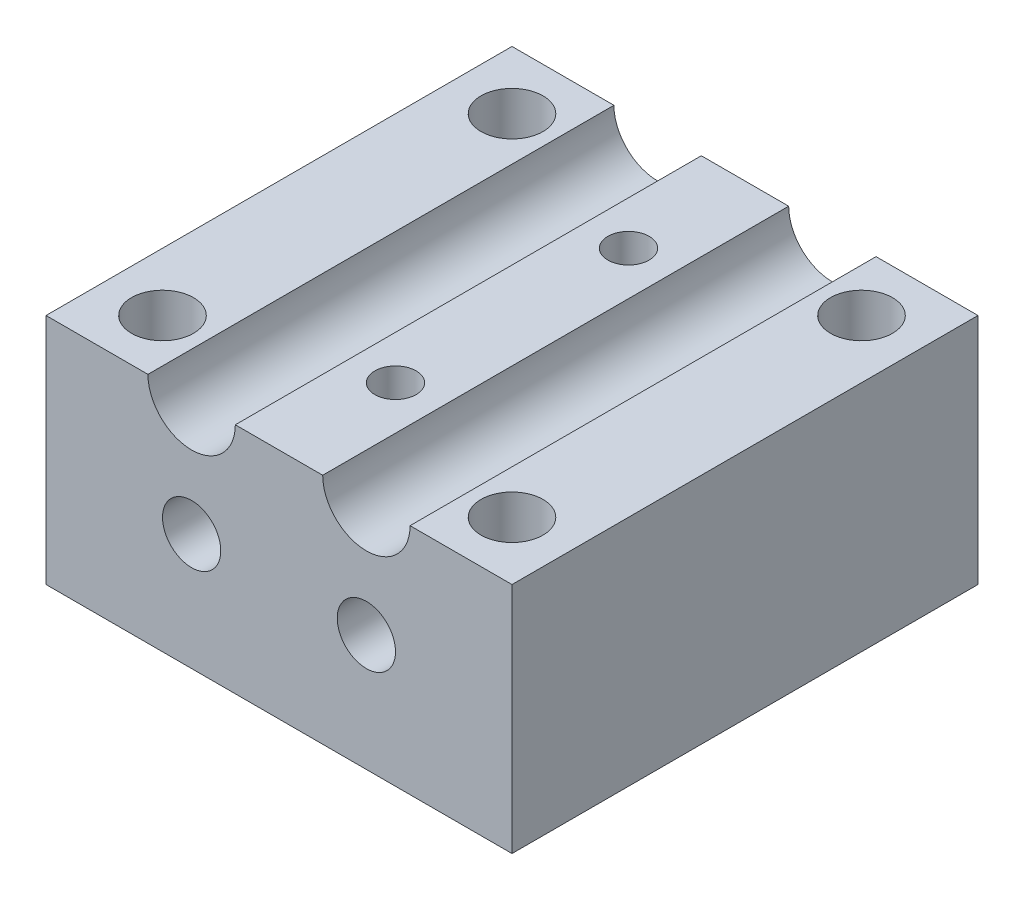
SolidWorks part; units mm, degrees
ref_plane "Front Plane" through (0, 0, 0) normal (0, 0, 1) x (1, 0, 0)
ref_plane "Top Plane" through (0, 0, 0) normal (0, 1, 0) x (1, 0, 0)
ref_plane "Right Plane" through (0, 0, 0) normal (1, 0, 0) x (0, 0, -1)
sketch "Sketch1" plane through (0, 0, 0) normal (0, 1, 0) x (1, 0, 0)
  line L1 (25.4, 25.4) -> (-25.4, 25.4)
  line L2 (25.4, 25.4) -> (25.4, -25.4)
  line L3 (25.4, -25.4) -> (-25.4, -25.4)
  line L4 (-25.4, 25.4) -> (-25.4, -25.4)
  line L5 (25.4, 25.4) -> (-25.4, -25.4) construction
  line L6 (25.4, -25.4) -> (-25.4, 25.4) construction
  point P0 (0, 0)
  dimension "D1" = 50.8
  dimension "D2" = 50.8
extrude "Boss-Extrude1" add sketch "Sketch1" along normal blind 25.4
sketch "Sketch2" plane through (0, 0, 25.4) normal (0, 0, 1) x (1, 0, 0)
  line L0 (-25.4, 25.4) -> (25.4, 25.4) construction
  line L1 (25.4, 25.4) -> (-25.4, 25.4) construction
  circle A0 centre (-9.525, 25.4) radius 4.7625
  circle A1 centre (9.525, 25.4) radius 4.7625
  point P6 (0, 25.4)
  dimension "D1" = 9.525
  dimension "D2" = 19.05
  dimension "D3" = 9.525
extrude "Cut-Extrude1" cut sketch "Sketch2" against normal through all
hole_wizard "1/4 Clearance Hole1" positions "Sketch5" profile "Sketch4" hole size "1/4" standard "ANSI Inch" end condition through all
sketch "Sketch5" plane through (0, 25.4, 0) normal (0, 1, 0) x (1, 0, 0)
  point P0 (-19.05, 19.05)
  point P2 (-19.05, -19.05)
  point P4 (19.05, -19.05)
  point P6 (19.05, 19.05)
sketch "Sketch4" plane through (-19.05, 25.4, -19.05) normal (1, 0, 0) x (0, 0, 1)
  line L0 (0, 0) -> (0, 25.4)
  line L1 (0, 25.4) -> (3.3782, 25.4)
  line L2 (3.3782, 25.4) -> (3.3782, 0)
  line L5 (3.3782, 0) -> (0, 0)
  line L11 (0, -6.35) -> (0, 107.95) construction
  dimension "Thru Hole Dia." = 6.7564
  dimension "Thru Hole Depth" = 25.4
sketch "Sketch6" plane through (0, 0, 25.4) normal (0, 0, 1) x (1, 0, 0)
  line L0 (-25.4, 25.4) -> (-14.2875, 25.4) construction
  circle A0 centre (-9.525, 12.7) radius 3.175
  circle A1 centre (9.525, 12.7) radius 3.175
  dimension "D1" = 6.35
  dimension "D2" = 19.05
  dimension "D4" = 9.525
  dimension "D5" = 12.7
extrude "Cut-Extrude2" cut sketch "Sketch6" against normal through all
hole_wizard "#8 Clearance Hole1" positions "Sketch8" profile "Sketch7" hole size "#8" standard "ANSI Inch" end condition through all
sketch "Sketch8" plane through (0, 25.4, 0) normal (0, 1, 0) x (1, 0, 0)
  point P0 (0, 12.7)
  point P2 (0, -12.7)
sketch "Sketch7" plane through (0, 25.4, -12.7) normal (1, 0, 0) x (0, 0, 1)
  line L0 (0, 0) -> (0, 25.4)
  line L1 (0, 25.4) -> (2.2479, 25.4)
  line L2 (2.2479, 25.4) -> (2.2479, 0)
  line L5 (2.2479, 0) -> (0, 0)
  line L11 (0, -6.35) -> (0, 107.95) construction
  dimension "Thru Hole Dia." = 4.4958
  dimension "Thru Hole Depth" = 25.4
